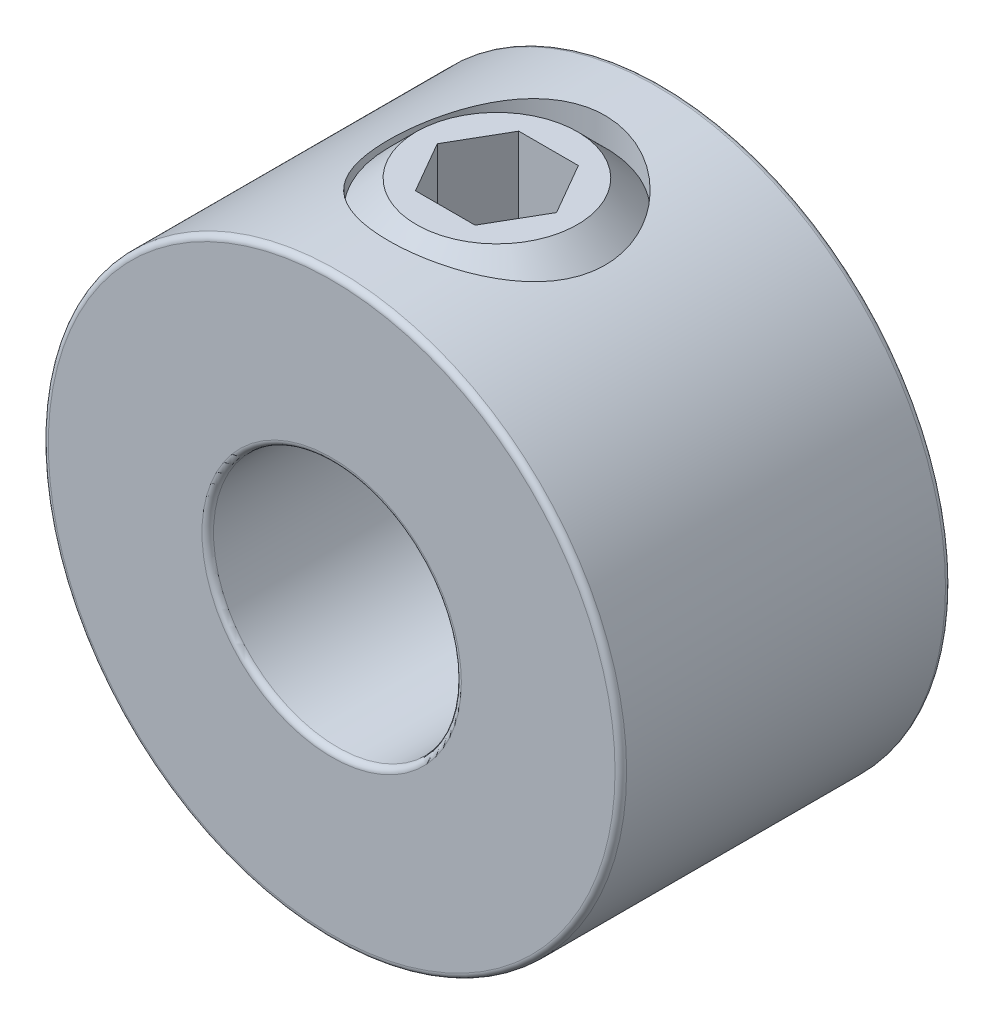
SolidWorks part; units mm, degrees
ref_plane "Front Plane" through (0, 0, 0) normal (0, 0, 1) x (1, 0, 0)
ref_plane "Top Plane" through (0, 0, 0) normal (0, 1, 0) x (1, 0, 0)
ref_plane "Right Plane" through (0, 0, 0) normal (1, 0, 0) x (0, 0, -1)
sketch "Sketch1" plane through (0, 0, 0) normal (0, 0, 1) x (1, 0, 0)
  circle A0 centre (0, 0) radius 5.5562
  circle A1 centre (0, 0) radius 2.3813
  point P4 (5.5562, 0)
  dimension "Bore Dia" = 4.7625
  dimension "OD" = 11.1125
extrude "Extrude1" add sketch "Sketch1" along normal mid plane 6.35
sketch "Sketch2" plane through (41.275, 0, 0) normal (0, -1, 0) x (0, 0, -1)
  line L0 (3.175, -41.275) -> (-3.175, -41.275) construction
  line L1 (-3.175, -35.7188) -> (-3.175, -46.8312) construction
  line L2 (3.175, -46.8312) -> (3.175, -35.7188) construction
  circle A0 centre (0, -41.275) radius 2.0828
  point P7 (0, -43.3578)
  dimension "Set Screw Dia" = 4.1656
extrude "Cut-Extrude1" cut sketch "Sketch2" against normal through all
fillet "Fillet1" radius 0.1111 4 edges at (2.3813, 0, -3.175) (2.3813, 0, 3.175) (5.5562, 0, -3.175) (5.5562, 0, 3.175)
sketch "Sketch3" plane through (0, 0, 0) normal (0, 0, 1) x (1, 0, 0)
  line L0 (-1.5473, 2.3813) -> (-0.6426, 2.3813)
  line L1 (0, 3.0238) -> (-0.6426, 2.3813)
  line L2 (0, 3.0238) -> (0, 5.5563)
  line L3 (0, 5.5563) -> (-1.5473, 5.5563)
  line L4 (-2.0828, 2.9167) -> (-2.0828, 5.0208)
  line L5 (0, 2.3813) -> (0, 0) construction
  line L6 (-2.0828, 2.9167) -> (-2.0828, 2.3813) construction
  line L7 (-2.0828, 2.3813) -> (-1.5473, 2.3813) construction
  line L8 (-2.0828, 5.0208) -> (-2.0828, 5.5563) construction
  line L9 (-1.5473, 2.3813) -> (-2.0828, 2.9167)
  line L10 (-2.0828, 5.0208) -> (-1.5473, 5.5563)
  line L11 (-2.0828, 5.5563) -> (-1.5473, 5.5563) construction
  line L12 (-0.6426, 2.3813) -> (0, 2.3813) construction
  line L13 (0, 2.3813) -> (0, 3.0238) construction
  circle A1 centre (0, 0) radius 2.3813 construction
  dimension "Screw Length" = 3.175
  dimension "D2" = 0.5355
  dimension "D1" = 0.6426
revolve "Revolve1" add sketch "Sketch3" angle 360 about L5
sketch "Sketch4" plane through (3.3734, 5.5562, 0) normal (0, -1, 0) x (0, 0, -1)
  line L1 (0, -2.2278) -> (-0.9922, -2.8006)
  line L2 (-0.9922, -2.8006) -> (-0.9922, -3.9463)
  line L3 (-0.9922, -3.9463) -> (0, -4.5191)
  line L4 (0, -4.5191) -> (0.9922, -3.9463)
  line L5 (0.9922, -3.9463) -> (0.9922, -2.8006)
  line L6 (0.9922, -2.8006) -> (0, -2.2278)
  circle A0 centre (0, -3.3734) radius 0.9922 construction
  circle A1 centre (0, -3.3734) radius 1.1457 construction
  dimension "D1" = 2.2914
  dimension "Hex Size" = 1.9844
extrude "Cut-Extrude2" cut sketch "Sketch4" along normal blind 1.9844
equation "\"D1@Fillet1\" = \"OD@Sketch1\"*.01"
equation "\"D1@Cut-Extrude2\" = \"Hex Size@Sketch4\""
equation "\"D2@Sketch3\" =(\"Set Screw Dia@Sketch2\"-\"D1@Sketch4\")/3.5"
equation "\"D1@Sketch3\" = \"D2@Sketch3\"*1.2"
